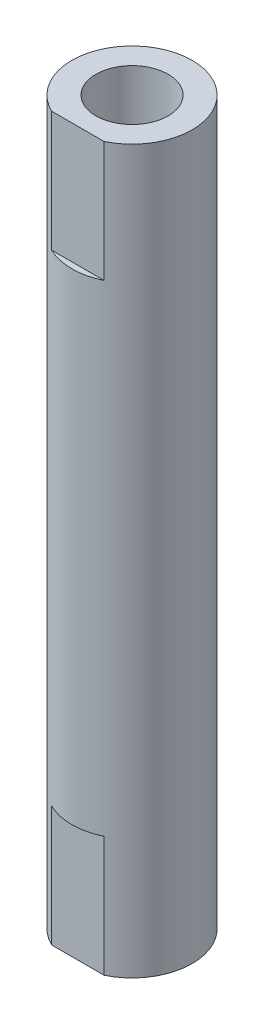
SolidWorks part; units mm, degrees
ref_plane "Front Plane" through (0, 0, 0) normal (0, 0, 1) x (1, 0, 0)
ref_plane "Top Plane" through (0, 0, 0) normal (0, 1, 0) x (1, 0, 0)
ref_plane "Right Plane" through (0, 0, 0) normal (1, 0, 0) x (0, 0, -1)
sketch "Sketch1" plane through (0, 0, 0) normal (0, 1, 0) x (1, 0, 0)
  circle A0 centre (0, 0) radius 5
  circle A1 centre (0, 0) radius 3
  dimension "D1" = 10
  dimension "D2" = 6
extrude "Boss-Extrude1" add sketch "Sketch1" along normal mid plane 60
sketch "Sketch2" plane through (0, -30, 0) normal (0, -1, 0) x (-1, 0, 0)
  line L0 (2.1794, -4.5) -> (-2.1794, -4.5)
  circle A1 centre (0, 0) radius 5 construction
  arc A2 (-2.1794, -4.5) -> (2.1794, -4.5) centre (0, 0) ccw
  dimension "D1" = 4.5
extrude "Cut-Extrude1" cut sketch "Sketch2" against normal blind 10
mirror "Mirror1" about plane through (0, 0, 0) normal (0, 1, 0) of "Cut-Extrude1"
